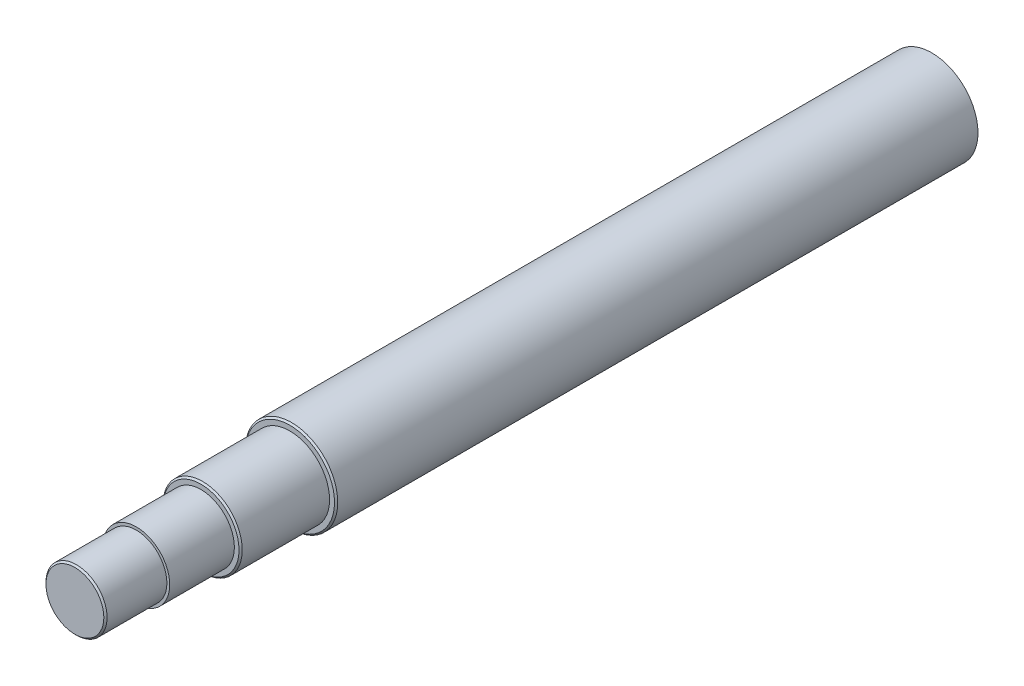
SolidWorks part; units mm, degrees
ref_plane "Front Plane" through (0, 0, 0) normal (0, 0, 1) x (1, 0, 0)
ref_plane "Top Plane" through (0, 0, 0) normal (0, 1, 0) x (1, 0, 0)
ref_plane "Right Plane" through (0, 0, 0) normal (1, 0, 0) x (0, 0, -1)
sketch "Sketch1" plane through (0, 0, 0) normal (0, 0, 1) x (1, 0, 0)
  circle A0 centre (0, 0) radius 28.575
  dimension "D1" = 57.15
extrude "Boss-Extrude1" add sketch "Sketch1" along normal blind 530
sketch "Sketch2" plane through (0, 0, 530) normal (0, 0, 1) x (1, 0, 0)
  circle A0 centre (0, 0) radius 18.9
  dimension "D1" = 37.8
extrude "Cut-Extrude4" cut sketch "Sketch2" against normal blind 38 flip side to cut contours A0
sketch "Sketch3" plane through (0, 0, 492) normal (0, 0, 1) x (1, 0, 0)
  circle A0 centre (0, 0) radius 20.64
  dimension "D1" = 41.28
extrude "Cut-Extrude5" cut sketch "Sketch3" against normal blind 40 flip side to cut
sketch "Sketch4" plane through (0, 0, 452) normal (0, 0, 1) x (1, 0, 0)
  circle A0 centre (0, 0) radius 24.5
  dimension "D1" = 49
extrude "Cut-Extrude6" cut sketch "Sketch4" against normal blind 55 flip side to cut
sketch "Sketch5" plane through (0, 0, 0) normal (0, 0, -1) x (-1, 0, 0)
  circle A0 centre (0, 0) radius 5
  dimension "D1" = 10
extrude "Boss-Extrude2" add sketch "Sketch5" along normal blind 5
chamfer "Chamfer1" distance 1 angle 45 3 edges at (28.575, 0, 397) (24.5, 0, 452) (18.9, 0, 530)
